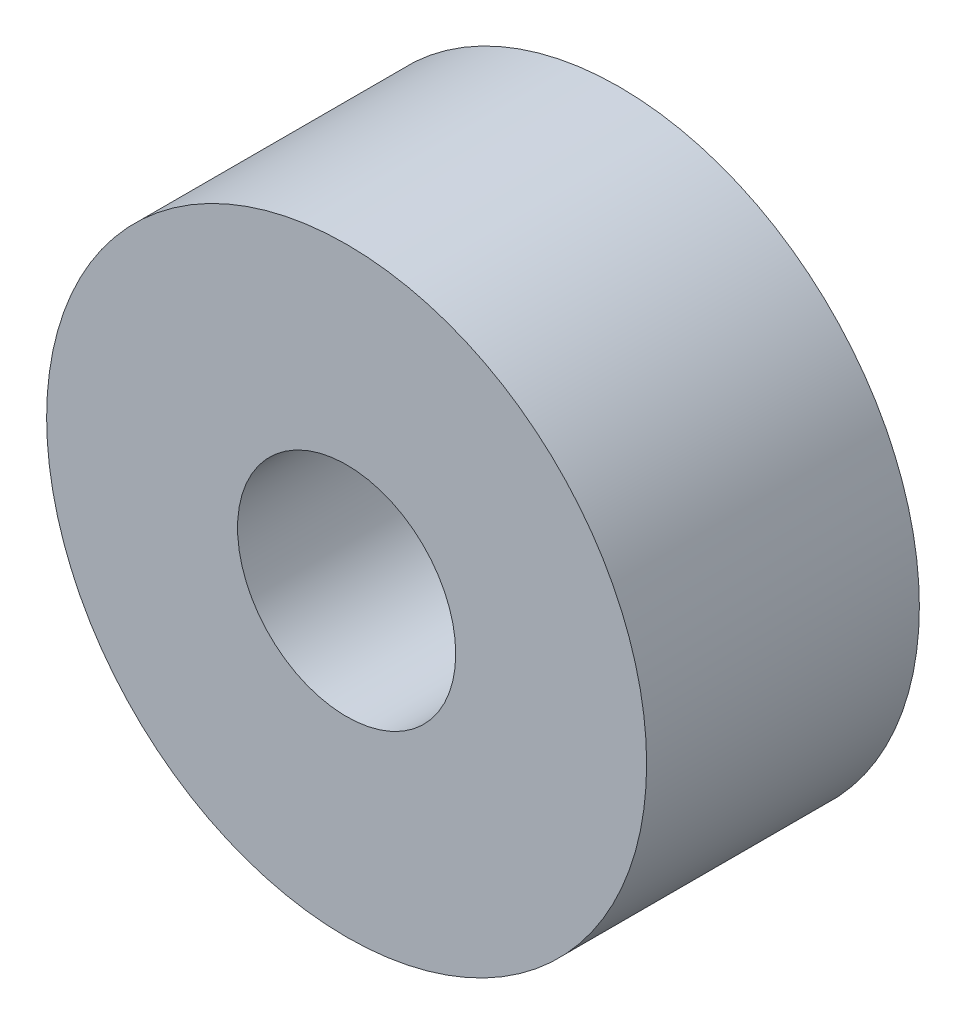
SolidWorks part; units mm, degrees
ref_plane "Front Plane" through (0, 0, 0) normal (0, 0, 1) x (1, 0, 0)
ref_plane "Top Plane" through (0, 0, 0) normal (0, 1, 0) x (1, 0, 0)
ref_plane "Right Plane" through (0, 0, 0) normal (1, 0, 0) x (0, 0, -1)
sketch "Sketch1" plane through (0, 0, 0) normal (0, 0, 1) x (1, 0, 0)
  circle A0 centre (0, 0) radius 11
  circle A1 centre (0, 0) radius 4
  dimension "D1" = 8
  dimension "D2" = 22
extrude "Boss-Extrude1" add sketch "Sketch1" along normal blind 10
